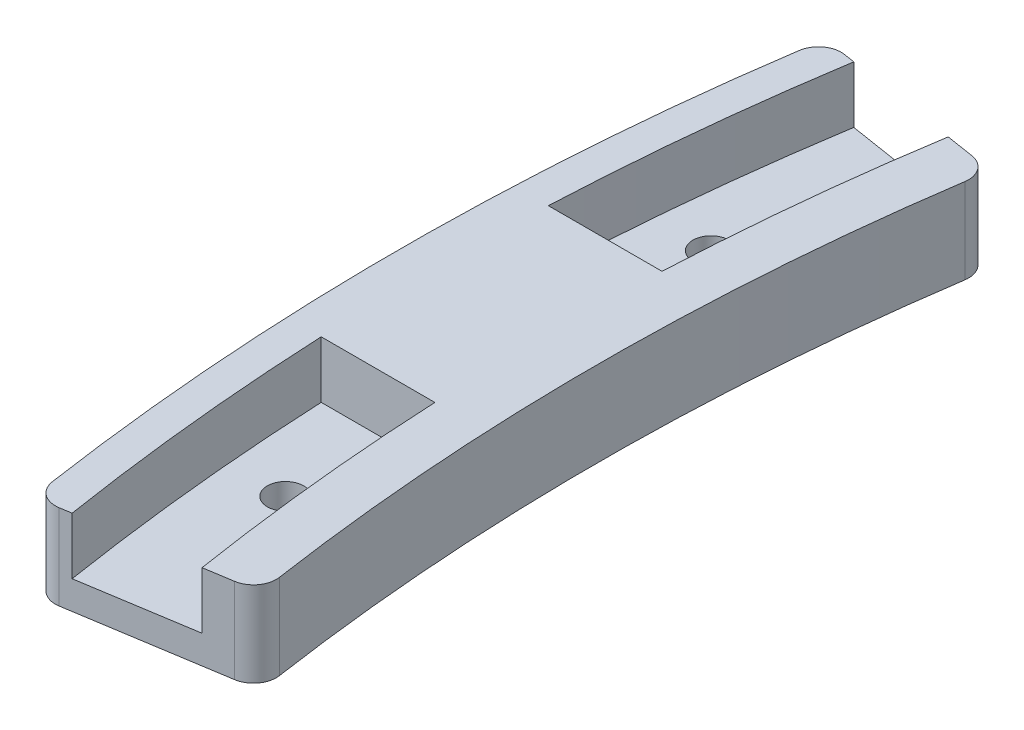
SolidWorks part; units mm, degrees
ref_plane "Front Plane" through (0, 0, 0) normal (0, 0, 1) x (1, 0, 0)
ref_plane "Top Plane" through (0, 0, 0) normal (0, 1, 0) x (1, 0, 0)
ref_plane "Right Plane" through (0, 0, 0) normal (1, 0, 0) x (0, 0, -1)
sketch "Sketch1" plane through (0, 0, 0) normal (0, 1, 0) x (1, 0, 0)
  line L0 (0, 0) -> (-217.2914, -34.4156) construction
  line L1 (0, 0) -> (-217.2914, 34.4156) construction
  line L2 (0, 0) -> (-215, 0) construction
  line L3 (-217.2914, 34.4156) -> (-207.4146, 32.8512)
  line L4 (-207.4146, -32.8512) -> (-217.2914, -34.4156)
  line L5 (0, 0) -> (-220.2545, -34.8849) construction
  line L6 (0, 0) -> (-220.2545, 34.8849) construction
  line L7 (-220.2545, 34.8849) -> (-202.97, 32.1473)
  line L8 (-220.2545, -34.8849) -> (-202.97, -32.1473)
  arc A0 (-217.2914, 34.4156) -> (-217.2914, -34.4156) centre (0, 0) ccw
  arc A1 (-207.4146, 32.8512) -> (-207.4146, -32.8512) centre (0, 0) ccw
  arc A2 (-212.353, -33.6334) -> (-212.353, 33.6334) centre (0, 0) cw construction
  arc A4 (-202.97, 32.1473) -> (-202.97, -32.1473) centre (0, 0) ccw
  arc A5 (-220.2545, 34.8849) -> (-220.2545, -34.8849) centre (0, 0) ccw
  dimension "D1" = 220
  dimension "D2" = 210
  dimension "D3" = 5
  dimension "D5" = 4.5
  dimension "D6" = 3
  dimension "D4" = 18
extrude "Boss-Extrude1" add sketch "Sketch1" along normal blind 10 contours A1 L3 A0 L4 | L7 A5 L8 A0 | A4 L7 A1 L8
ref_plane "Plane1" through (-215, 0, 0) normal (1, 0, 0) x (0, 0, -1)
sketch "Sketch15" plane through (0, 10, 0) normal (0, 1, 0) x (1, 0, 0)
  line L0 (-207.4146, -32.8512) -> (-217.2914, -34.4156) construction
  line L1 (-205, 10) -> (-225, 10)
  line L2 (-205, 10) -> (-205, -10)
  line L3 (-205, -10) -> (-225, -10)
  line L4 (-225, 10) -> (-225, -10)
  line L5 (-205, 10) -> (-225, -10) construction
  line L6 (-205, -10) -> (-225, 10) construction
  line L7 (-217.2914, 34.4156) -> (-207.4146, 32.8512) construction
  line L8 (-207.4146, -32.8512) -> (-217.2914, -34.4156)
  line L9 (-217.2914, 34.4156) -> (-207.4146, 32.8512)
  arc A2 (-207.4146, 32.8512) -> (-207.4146, -32.8512) centre (0, 0) ccw construction
  arc A3 (-217.2914, 34.4156) -> (-217.2914, -34.4156) centre (0, 0) ccw construction
  arc A4 (-207.4146, 32.8512) -> (-207.4146, -32.8512) centre (0, 0) ccw
  arc A5 (-217.2914, 34.4156) -> (-217.2914, -34.4156) centre (0, 0) ccw
  point P0 (-215, 0)
  line M5 (-220.2545, -34.8849) -> (-202.97, -32.1473)
  line M7 (-202.97, 32.1473) -> (-220.2545, 34.8849)
  dimension "D1" = 20
  dimension "D2" = 20
extrude "Cut-Extrude1" cut sketch "Sketch15" against normal blind 5 contours A5 L1 A4 M7 | L3 A5 A4 M5
ref_plane "Plane2" through (-215, 0, 0) normal (-1, 0, 0) x (0, 0, 1)
sketch "Sketch12" plane through (0, 0, 0) normal (0, 1, 0) x (1, 0, 0)
  line L0 (0, 0) -> (-214.1819, -18.7385) construction
  line L1 (0, 0) -> (-213.1606, -28.0631) construction
  line L2 (0, 0) -> (-215, 0) construction
  line L3 (0, 0) -> (-215, 0) construction
  line L4 (0, 0) -> (-214.1819, 18.7385) construction
  line L5 (0, 0) -> (-213.1606, 28.0631) construction
  arc A0 (-212.353, 33.6334) -> (-212.353, -33.6334) centre (0, 0) ccw construction
  dimension "D1" = 10
  dimension "D2" = 15
hole_wizard "Ø3.2 (3.2) Diameter Hole1" positions "Sketch18" profile "Sketch17" hole size "Ø3.2" standard "ISO" end condition through all
sketch "Sketch18" plane through (0, 0, 0) normal (0, -1, 0) x (-1, 0, 0)
  point P3 (214.1819, -18.7385)
  point P6 (214.1819, 18.7385)
sketch "Sketch17" plane through (-214.1819, 0, 18.7385) normal (1, 0, 0) x (0, 0, -1)
  line L0 (0, 0) -> (0, 10)
  line L1 (0, 10) -> (1.6, 10)
  line L2 (1.6, 10) -> (1.6, 0)
  line L5 (1.6, 0) -> (0, 0)
  line L11 (0, -6.35) -> (0, 107.95) construction
  dimension "Thru Hole Dia." = 3.2
  dimension "Thru Hole Depth" = 10
fillet "Fillet1" radius 2 4 edges at (-220.2545, 5, -34.8849) (-202.97, 5, -32.1473) (-220.2545, 5, 34.8849) (-202.97, 5, 32.1473)
sketch "Sketch19" plane through (0, 0, 0) normal (0, -1, 0) x (1, 0, 0)
  line L2 (-218.2702, -34.5706) -> (-204.9358, -32.4586)
  line L3 (-204.9358, 32.4586) -> (-218.2702, 34.5706)
  line L4 (-218.2702, -34.5706) -> (-204.9358, -32.4586)
  line L5 (-204.9358, 32.4586) -> (-218.2702, 34.5706)
  arc A6 (-220.5612, 32.8902) -> (-220.5612, -32.8902) centre (0, 0) ccw
  arc A7 (-220.5612, -32.8902) -> (-218.2702, -34.5706) centre (-218.5831, -32.5952) ccw
  arc A8 (-204.9358, -32.4586) -> (-203.2704, -30.1895) centre (-205.2487, -30.4833) ccw
  arc A9 (-203.2704, 30.1895) -> (-203.2704, -30.1895) centre (0, 0) ccw
  arc A10 (-203.2704, 30.1895) -> (-204.9358, 32.4586) centre (-205.2487, 30.4833) ccw
  arc A11 (-218.2702, 34.5706) -> (-220.5612, 32.8902) centre (-218.5831, 32.5952) ccw
  arc A12 (-220.5612, 32.8902) -> (-220.5612, -32.8902) centre (0, 0) ccw
  arc A13 (-220.5612, -32.8902) -> (-218.2702, -34.5706) centre (-218.5831, -32.5952) ccw
  arc A14 (-204.9358, -32.4586) -> (-203.2704, -30.1895) centre (-205.2487, -30.4833) ccw
  arc A15 (-203.2704, 30.1895) -> (-203.2704, -30.1895) centre (0, 0) ccw
  arc A16 (-203.2704, 30.1895) -> (-204.9358, 32.4586) centre (-205.2487, 30.4833) ccw
  arc A17 (-218.2702, 34.5706) -> (-220.5612, 32.8902) centre (-218.5831, 32.5952) ccw
  dimension "D1" = 0
extrude "Cut-Extrude2" cut sketch "Sketch19" against normal blind 2.5
